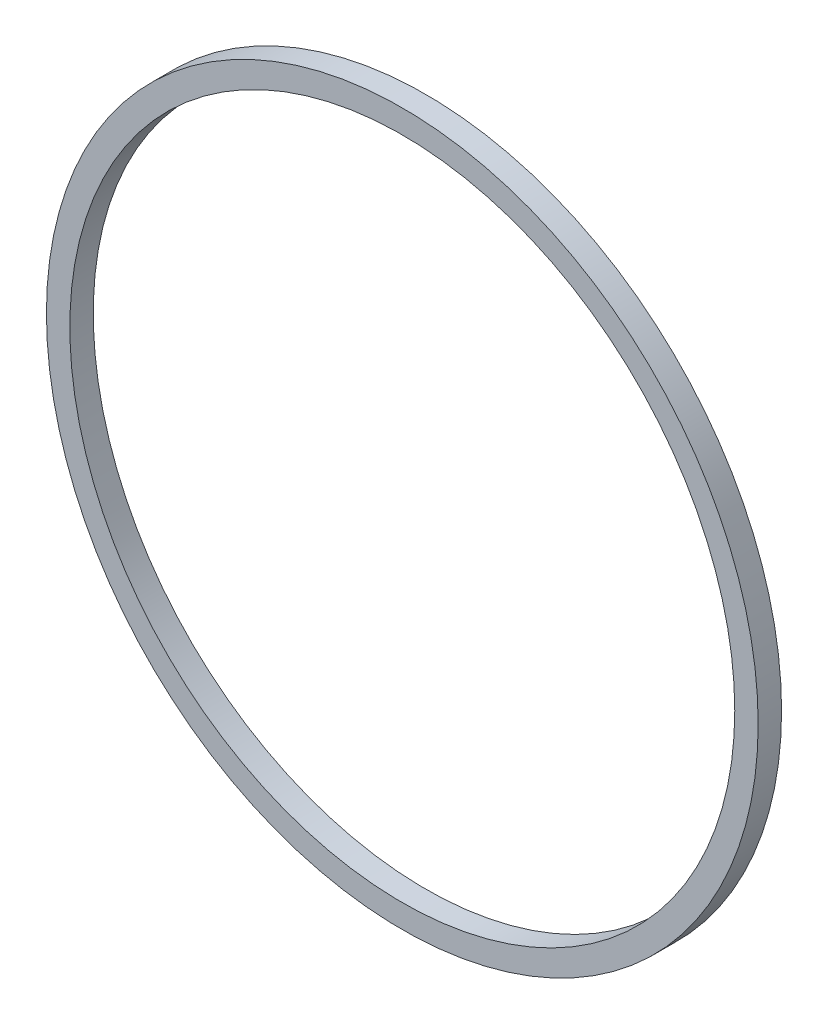
SolidWorks part; units mm, degrees
ref_plane "Front Plane" through (0, 0, 0) normal (0, 0, 1) x (1, 0, 0)
ref_plane "Top Plane" through (0, 0, 0) normal (0, 1, 0) x (1, 0, 0)
ref_plane "Right Plane" through (0, 0, 0) normal (1, 0, 0) x (0, 0, -1)
sketch "Sketch1" plane through (0, 0, 0) normal (0, 0, 1) x (1, 0, 0)
  line L0 (-27.0383, 0) -> (27.0383, 0) construction
  line L1 (-25.2603, 0) -> (25.2603, 0) construction
  line L2 (-19.119, 19.119) -> (19.119, -19.119) construction
  point P3 (25.2603, 0)
  point P4 (0, 0)
  point P8 (0, 0)
  point P9 (0, 0)
  point P10 (-27.0383, 0)
  point P11 (-25.2603, 0)
  point P14 (0, 0)
  point P15 (19.119, -19.119)
  point P16 (27.0383, 0)
  dimension "Actual OD" = 54.0766
  dimension "Actual ID" = 50.5206
  dimension "Actual Width" = 1.778
  dimension "D1" = 45
sketch "Sketch2" plane through (0, 0, 0) normal (0, 1, 0) x (1, 0, 0)
  line L1 (-26.1493, 0.889) -> (-26.1493, -0.889) construction
  line L2 (0, -0.889) -> (0, 0.889) construction
  line L3 (-27.0383, 0) -> (27.0383, 0) construction
  line L4 (-27.0383, -0.889) -> (-25.2603, -0.889)
  line L5 (-27.0383, -0.889) -> (-27.0383, 0.889)
  line L6 (-27.0383, 0.889) -> (-25.2603, 0.889)
  line L7 (-25.2603, -0.889) -> (-25.2603, 0.889)
  line L9 (-27.0383, 0) -> (-25.2603, 0) construction
  point P0 (-26.1493, 0)
  point P12 (0, 0)
revolve "Revolve1" add sketch "Sketch2" angle 360 about L2
sketch "Sketch3" plane through (0, 0, 0) normal (1, 0, 0) x (0, 0, -1)
  line L0 (-0.889, 0) -> (0.889, 0) construction
  line L1 (-0.889, -18.9452) -> (-0.889, 18.9452) construction
  point P4 (0, 0)
  point P7 (-0.889, 0)
  point P9 (-0.889, -18.9452)
  dimension "D1" = 1.778
  dimension "D2" = 37.8905
equation "\"D1@Sketch3\"=\"Actual Width@Sketch1\""
equation "\"D2@Sketch3\"=\"Actual ID@Sketch1\"*.75"
